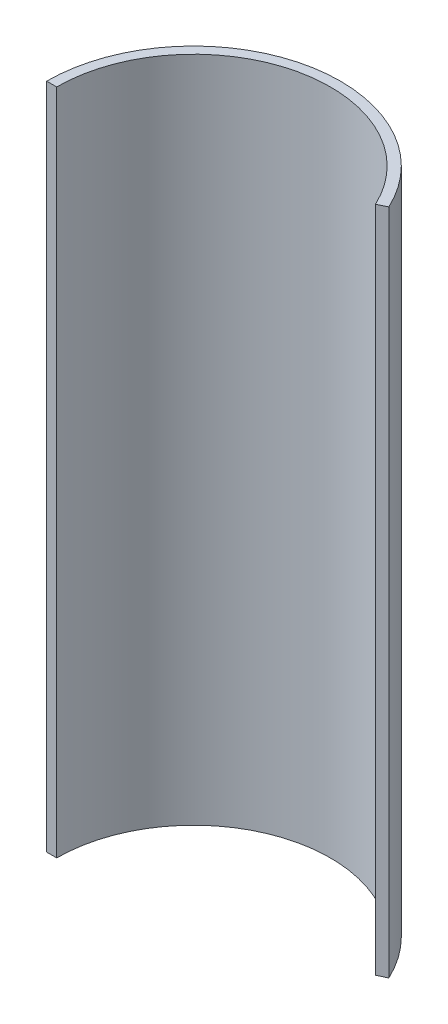
SolidWorks part; units mm, degrees
ref_plane "前视基准面" through (0, 0, 0) normal (0, 0, 1) x (1, 0, 0)
ref_plane "上视基准面" through (0, 0, 0) normal (0, 1, 0) x (1, 0, 0)
ref_plane "右视基准面" through (0, 0, 0) normal (1, 0, 0) x (0, 0, -1)
sketch "草图1" plane through (0, 0, 0) normal (0, 1, 0) x (1, 0, 0)
  line L0 (-22, 0) -> (-20.5, 0)
  line L1 (20.5, 0) -> (22, 0)
  line L2 (0, 0) -> (0, 20.5) construction
  arc A0 (22, 0) -> (0.8, 21.9854) centre (0, 0) ccw
  arc A1 (20.5, 0) -> (-20.5, 0) centre (0, 0) ccw
  circle A2 centre (0, 0) radius 20.5 construction
  circle A3 centre (0, 0) radius 22 construction
  arc A4 (0.8, 21.9854) -> (-22, 0) centre (0, 0) ccw
  dimension "D1" = 44
  dimension "D2" = 1.5
extrude "凸台-拉伸1" add sketch "草图1" along normal mid plane 100
sketch "草图2" plane through (0, 0, 0) normal (0, 1, 0) x (1, 0, 0)
  line L0 (0, 0) -> (0, 17.3619) construction
  line L1 (-0.8, 22.8) -> (-0.8, 21.9854)
  line L2 (20.5, 0) -> (22, 0)
  line L3 (-22, 0) -> (-20.5, 0)
  line L5 (0.8, 21.9854) -> (0.8, 22.8)
  line L6 (0.8, 22.8) -> (-0.8, 22.8)
  line L7 (0, 22) -> (0, 27.3307) construction
  arc A2 (20.5, 0) -> (-20.5, 0) centre (0, 0) ccw
  arc A3 (22, 0) -> (-22, 0) centre (0, 0) ccw
  arc A5 (0.8, 21.9854) -> (-0.8, 21.9854) centre (0, 0) ccw
  dimension "D2" = 0.8
  dimension "D3" = 0.8
  dimension "D4" = 22.8
  dimension "D1" = 0
extrude "凸台-拉伸2" add sketch "草图2" along normal mid plane 15
sketch "草图3" plane through (0, 50, 0) normal (0, 1, 0) x (1, 0, 0)
  line L0 (0, 0) -> (22, 10.2588)
  line L1 (0, 0) -> (22, 0)
  line L2 (22, 10.2588) -> (22, 0)
  arc A0 (22, 0) -> (-22, 0) centre (0, 0) ccw construction
  dimension "D1" = 25
extrude "切除-拉伸1" cut sketch "草图3" against normal through all
